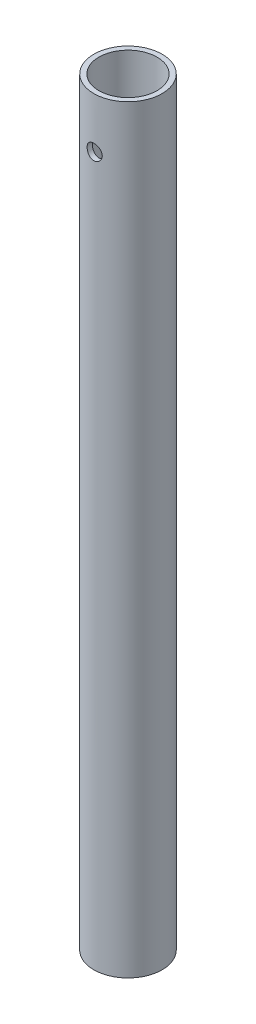
SolidWorks part; units mm, degrees
ref_plane "Alzado" through (0, 0, 0) normal (0, 0, 1) x (1, 0, 0)
ref_plane "Planta" through (0, 0, 0) normal (0, 1, 0) x (1, 0, 0)
ref_plane "Vista lateral" through (0, 0, 0) normal (1, 0, 0) x (0, 0, -1)
sketch "Croquis1" plane through (0, 0, 0) normal (0, 1, 0) x (1, 0, 0)
  circle A0 centre (0, 0) radius 13.5
  dimension "D1" = 27
extrude "Saliente-Extruir1" add sketch "Croquis1" along normal blind 300
sketch "Croquis2" plane through (0, 0, 0) normal (0, -1, 0) x (1, 0, 0)
  circle A0 centre (0, 0) radius 3
  dimension "D1" = 6
extrude "Cortar-Extruir1" cut sketch "Croquis2" against normal blind 15
sketch "Croquis4" plane through (0, 300, 0) normal (0, 1, 0) x (1, 0, 0)
  circle A0 centre (0, 0) radius 11.5
  dimension "D1" = 23
extrude "Cortar-Extruir4" cut sketch "Croquis4" against normal blind 50
sketch "Croquis5" plane through (0, 0, 0) normal (0, 0, 1) x (1, 0, 0)
  line L0 (0, 300) -> (0, 280)
  line L1 (11.5, 300) -> (-11.5, 300) construction
  circle A0 centre (0, 280) radius 3
  dimension "D2" = 6
  dimension "D1" = 20
extrude "Cortar-Extruir5" cut sketch "Croquis5" against normal through all both and the other way through all
